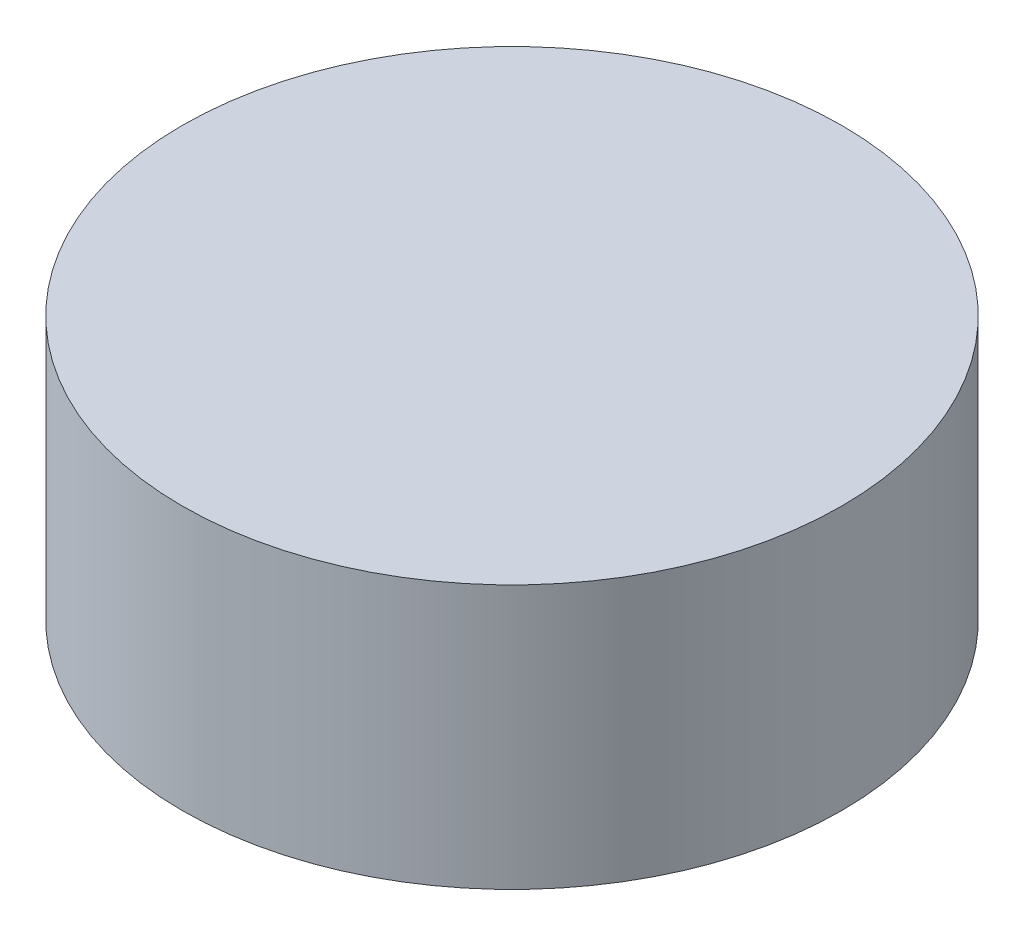
SolidWorks part; units mm, degrees
material "PVC 0.007 Plasticized"
ref_plane "Front Plane" through (0, 0, 0) normal (0, 0, 1) x (1, 0, 0)
ref_plane "Top Plane" through (0, 0, 0) normal (0, 1, 0) x (1, 0, 0)
ref_plane "Right Plane" through (0, 0, 0) normal (1, 0, 0) x (0, 0, -1)
sketch "Sketch1" plane through (0, 0, 0) normal (0, 1, 0) x (1, 0, 0)
  circle A0 centre (0, 0) radius 3.75
  dimension "D1" = 7.5
extrude "Boss-Extrude1" add sketch "Sketch1" along normal blind 3
